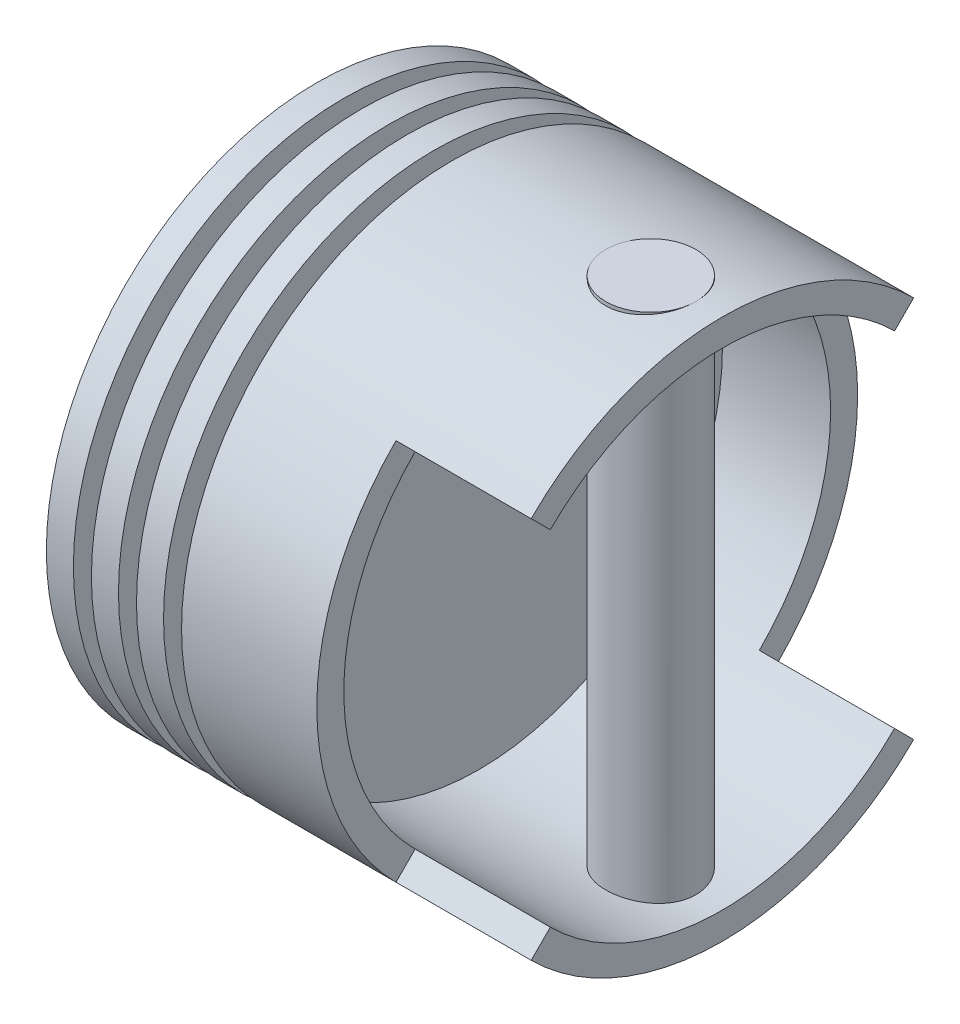
SolidWorks part; units mm, degrees
ref_plane "Front Plane" through (0, 0, 0) normal (0, 0, 1) x (1, 0, 0)
ref_plane "Top Plane" through (0, 0, 0) normal (0, 1, 0) x (1, 0, 0)
ref_plane "Right Plane" through (0, 0, 0) normal (1, 0, 0) x (0, 0, -1)
sketch "Sketch1" plane through (0, 0, 0) normal (1, 0, 0) x (0, 0, -1)
  circle A0 centre (0, 0) radius 30
  dimension "D1" = 60
extrude "Boss-Extrude1" add sketch "Sketch1" along normal blind 3
sketch "Sketch2" plane through (3, 0, 0) normal (1, 0, 0) x (0, 0, -1)
  line L1 (-3.5, 25) -> (3.5, 25)
  line L2 (-3.5, 25) -> (-3.5, -25)
  line L3 (-3.5, -25) -> (3.5, -25)
  line L4 (3.5, 25) -> (3.5, -25)
  line L5 (-3.5, 25) -> (3.5, -25) construction
  line L6 (-3.5, -25) -> (3.5, 25) construction
  point P0 (0, 0)
  dimension "D1" = 50
  dimension "D2" = 7
extrude "Boss-Extrude2" add sketch "Sketch2" along normal blind 2
sketch "Sketch3" plane through (5, 0, 0) normal (1, 0, 0) x (0, 0, -1)
  circle A0 centre (0, 0) radius 30
extrude "Boss-Extrude3" add sketch "Sketch3" along normal blind 3
sketch "Sketch4" plane through (8, 0, 0) normal (1, 0, 0) x (0, 0, -1)
  line L1 (-3.5, 25) -> (3.5, 25)
  line L2 (-3.5, 25) -> (-3.5, -25)
  line L3 (-3.5, -25) -> (3.5, -25)
  line L4 (3.5, 25) -> (3.5, -25)
  line L5 (-3.5, 25) -> (3.5, -25) construction
  line L6 (-3.5, -25) -> (3.5, 25) construction
  point P0 (0, 0)
  dimension "D1" = 50
  dimension "D2" = 7
extrude "Boss-Extrude4" add sketch "Sketch4" along normal blind 2
sketch "Sketch5" plane through (10, 0, 0) normal (1, 0, 0) x (0, 0, -1)
  circle A0 centre (0, 0) radius 30
extrude "Boss-Extrude5" add sketch "Sketch5" along normal blind 3
sketch "Sketch6" plane through (13, 0, 0) normal (1, 0, 0) x (0, 0, -1)
  line L1 (3.5, 25) -> (-3.5, 25)
  line L2 (3.5, 25) -> (3.5, -25)
  line L3 (3.5, -25) -> (-3.5, -25)
  line L4 (-3.5, 25) -> (-3.5, -25)
  line L5 (3.5, 25) -> (-3.5, -25) construction
  line L6 (3.5, -25) -> (-3.5, 25) construction
  point P0 (0, 0)
  dimension "D1" = 7
  dimension "D2" = 50
extrude "Boss-Extrude6" add sketch "Sketch6" along normal blind 2
sketch "Sketch7" plane through (15, 0, 0) normal (1, 0, 0) x (0, 0, -1)
  circle A0 centre (0, 0) radius 30
extrude "Boss-Extrude7" add sketch "Sketch7" along normal blind 30
sketch "Sketch8" plane through (45, 0, 0) normal (1, 0, 0) x (0, 0, -1)
  circle A0 centre (0, 0) radius 27
  dimension "D1" = 54
extrude "Cut-Extrude3" cut sketch "Sketch8" against normal blind 27
sketch "Sketch9" plane through (45, 0, 0) normal (1, 0, 0) x (0, 0, -1)
  line L1 (19.0919, 19.0919) -> (21.2132, 21.2132) construction
  line L2 (27, 0) -> (30, 0) construction
  line L3 (19.0919, -19.0919) -> (21.2132, -21.2132) construction
  line L5 (-19.0919, -19.0919) -> (-21.2132, -21.2132) construction
  line L6 (-27, 0) -> (-30, 0) construction
  line L7 (-19.0919, 19.0919) -> (-21.2132, 21.2132) construction
  line L8 (21.2132, 21.2132) -> (19.0919, 19.0919)
  line L9 (21.2132, -21.2132) -> (19.0919, -19.0919)
  line L10 (-21.2132, 21.2132) -> (-19.0919, 19.0919)
  line L11 (-21.2132, -21.2132) -> (-19.0919, -19.0919)
  arc A1 (21.2132, 21.2132) -> (21.2132, -21.2132) centre (0, 0) cw
  arc A2 (19.0919, 19.0919) -> (19.0919, -19.0919) centre (0, 0) cw
  circle A3 centre (0, 0) radius 27 construction
  arc A4 (-19.0919, -19.0919) -> (-19.0919, 19.0919) centre (0, 0) cw
  arc A5 (-21.2132, -21.2132) -> (-21.2132, 21.2132) centre (0, 0) cw
  point P16 (0, 0)
  point P26 (0, 0)
  dimension "D2" = 2
extrude "Cut-Extrude6" cut sketch "Sketch9" against normal blind 15
sketch "Sketch14" plane through (0, 0, 0) normal (0, 1, 0) x (1, 0, 0)
  circle A0 centre (37.0568, 0) radius 5
  dimension "D1" = 10
extrude "Boss-Extrude11" add sketch "Sketch14" along normal through all and the other way through all
